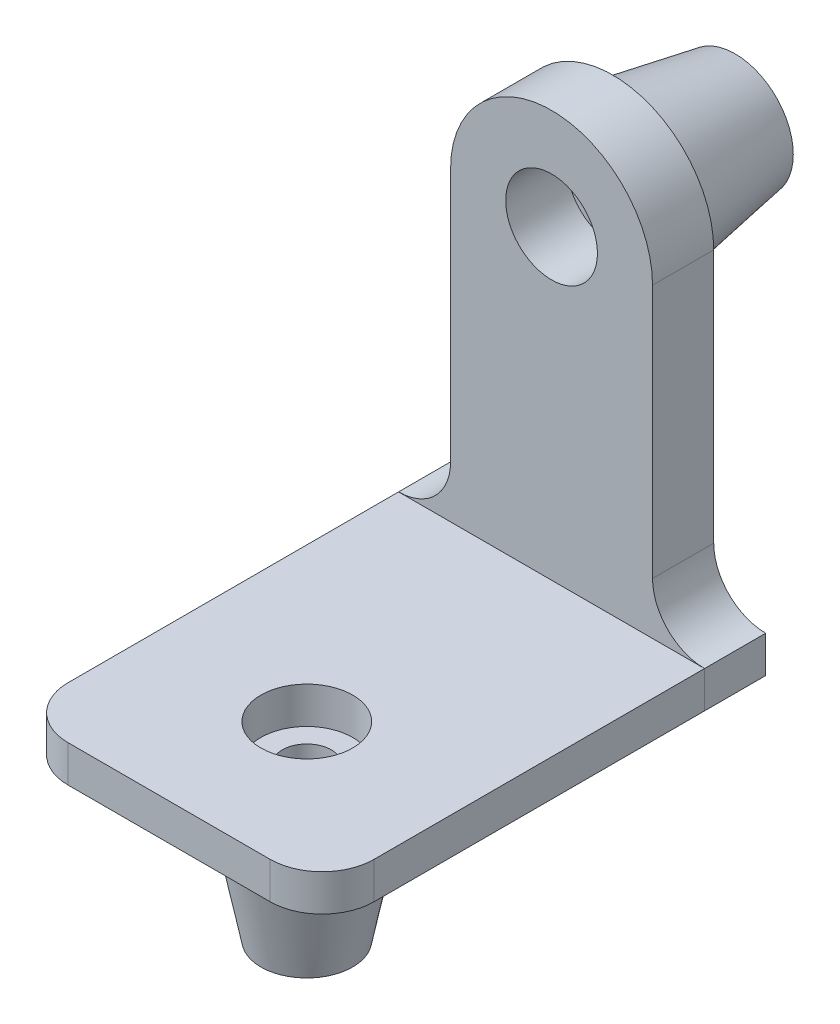
SolidWorks part; units mm, degrees
ref_plane "Alzado" through (0, 0, 0) normal (0, 0, 1) x (1, 0, 0)
ref_plane "Planta" through (0, 0, 0) normal (0, 1, 0) x (1, 0, 0)
ref_plane "Vista lateral" through (0, 0, 0) normal (1, 0, 0) x (0, 0, -1)
sketch "Croquis1" plane through (0, 0, 0) normal (0, 0, 1) x (1, 0, 0)
  line L0 (-50, 0) -> (50, 0)
  line L1 (-33, 100) -> (-33, 17)
  line L2 (33, 100) -> (33, 17)
  line L3 (0, 0) -> (0, 100) construction
  arc A0 (33, 100) -> (-33, 100) centre (0, 100) ccw
  arc A1 (33, 17) -> (50, 0) centre (50, 17) ccw
  arc A2 (-50, 0) -> (-33, 17) centre (-50, 17) ccw
  circle A3 centre (0, 100) radius 15
  point P4 (0, 0)
  dimension "D2" = 33
  dimension "D3" = 17
  dimension "D4" = 17
  dimension "D6" = 30
  dimension "D1" = 100
  dimension "D5" = 100
extrude "Saliente-Extruir1" add sketch "Croquis1" against normal blind 20
ref_plane "Plano1" through (0, 0, -20) normal (0, 0, 1) x (1, 0, 0)
sketch "Croquis3" plane through (0, 0, -20) normal (0, 0, 1) x (1, 0, 0)
  circle A0 centre (0, 100) radius 26
  dimension "D1" = 52
ref_plane "Plano2" through (0, 0, -60) normal (0, 0, 1) x (1, 0, 0)
sketch "Croquis4" plane through (0, 0, -60) normal (0, 0, 1) x (1, 0, 0)
  circle A0 centre (0, 100) radius 19
  dimension "D1" = 38
loft "Recubrir1" add profiles "Croquis4", "Croquis3"
sketch "Croquis5" plane through (0, 0, -20) normal (0, 0, 1) x (1, 0, 0)
  circle A0 centre (0, 100) radius 10
  dimension "D1" = 20
extrude "Cortar-Extruir1" cut sketch "Croquis5" against normal through all
ref_plane "Plano3" through (0, 0, 0) normal (0, 1, 0) x (1, 0, 0)
sketch "Croquis6" plane through (0, 0, 0) normal (0, 1, 0) x (1, 0, 0)
  line L0 (50, 0) -> (50, -125)
  line L1 (50, -125) -> (-50, -125)
  line L2 (-50, -125) -> (-50, 0)
  line L3 (-50, 0) -> (50, 0)
  circle A0 centre (0, -80) radius 15
  point P9 (0, -61.6531)
  dimension "D2" = 30
  dimension "D1" = 80
  dimension "D3" = 125
extrude "Saliente-Extruir2" add sketch "Croquis6" against normal blind 12 separate body
fillet "Redondeo1" radius 17 2 edges at (-50, -6, 125) (50, -6, 125)
sketch "Croquis7" plane through (0, -12, 0) normal (0, -1, 0) x (1, 0, 0)
  circle A0 centre (0, 80) radius 15
  circle A1 centre (0, 80) radius 15 construction
ref_plane "Plano4" through (0, -62, 0) normal (0, 1, 0) x (1, 0, 0)
sketch "Croquis8" plane through (0, -62, 0) normal (0, 1, 0) x (1, 0, 0)
  circle A0 centre (0, -80) radius 15
  dimension "D1" = 30
sketch "Croquis9" plane through (0, -12, 0) normal (0, -1, 0) x (1, 0, 0)
  circle A0 centre (0, 80) radius 25
  dimension "D1" = 50
loft "Recubrir2" add profiles "Croquis9", "Croquis8"
sketch "Croquis10" plane through (0, -12, 0) normal (0, 1, 0) x (1, 0, 0)
  circle A0 centre (0, -80) radius 8
  dimension "D1" = 16
extrude "Cortar-Extruir2" cut sketch "Croquis10" against normal through all
sketch "Croquis11" plane through (0, 0, 0) normal (0, -1, 0) x (1, 0, 0)
  line L0 (-50, 0) -> (-50, -20)
  line L1 (-50, -20) -> (50, -20)
  line L2 (50, -20) -> (50, 0)
  line L3 (50, 0) -> (-50, 0)
extrude "Saliente-Extruir3" add sketch "Croquis11" along normal blind 12 separate body
